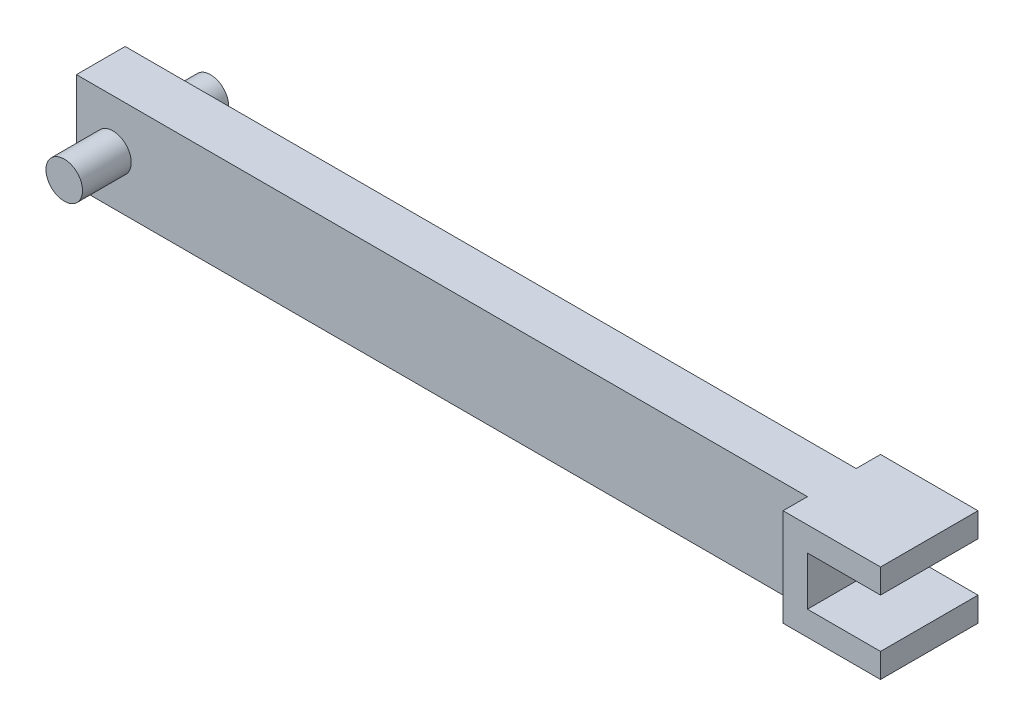
SolidWorks part; units mm, degrees
ref_plane "Front Plane" through (0, 0, 0) normal (0, 0, 1) x (1, 0, 0)
ref_plane "Top Plane" through (0, 0, 0) normal (0, 1, 0) x (1, 0, 0)
ref_plane "Right Plane" through (0, 0, 0) normal (1, 0, 0) x (0, 0, -1)
sketch "Sketch1" plane through (0, 0, 0) normal (0, 0, 1) x (1, 0, 0)
  line L1 (-150, 20) -> (150, 20)
  line L2 (-150, 20) -> (-150, -20)
  line L3 (-150, -20) -> (150, -20)
  line L4 (150, 20) -> (150, -20)
  line L5 (-150, 20) -> (150, -20) construction
  line L6 (-150, -20) -> (150, 20) construction
  point P0 (0, 0)
  dimension "D1" = 300
  dimension "D2" = 40
extrude "Boss-Extrude1" add sketch "Sketch1" along normal mid plane 20
sketch "Sketch2" plane through (0, 0, 0) normal (0, 0, 1) x (1, 0, 0)
  line L0 (-150, 20) -> (-150, -20) construction
  circle A0 centre (-135, 0) radius 7.5
  dimension "D1" = 15
  dimension "D2" = 15
extrude "Boss-Extrude2" add sketch "Sketch2" along normal mid plane 60
sketch "Sketch3" plane through (150, 0, 0) normal (1, 0, 0) x (0, 0, -1)
  line L1 (-20, -20) -> (20, -20)
  line L2 (-20, -20) -> (-20, 20)
  line L3 (-20, 20) -> (20, 20)
  line L4 (20, -20) -> (20, 20)
  line L5 (-20, -20) -> (20, 20) construction
  line L6 (-20, 20) -> (20, -20) construction
  point P0 (0, 0)
  dimension "D1" = 40
  dimension "D2" = 40
extrude "Boss-Extrude3" add sketch "Sketch3" along normal blind 40
sketch "Sketch4" plane through (0, 0, 20) normal (0, 0, 1) x (1, 0, 0)
  line L0 (190, 20) -> (190, -20) construction
  line L1 (160, -10) -> (220, -10)
  line L2 (160, -10) -> (160, 10)
  line L3 (160, 10) -> (220, 10)
  line L4 (220, -10) -> (220, 10)
  line L5 (160, -10) -> (220, 10) construction
  line L6 (160, 10) -> (220, -10) construction
  line L7 (190, 20) -> (150, 20) construction
  line L8 (150, -20) -> (150, 20) construction
  point P0 (190, 0)
  dimension "D1" = 10
  dimension "D2" = 10
extrude "Cut-Extrude1" cut sketch "Sketch4" against normal blind 58
